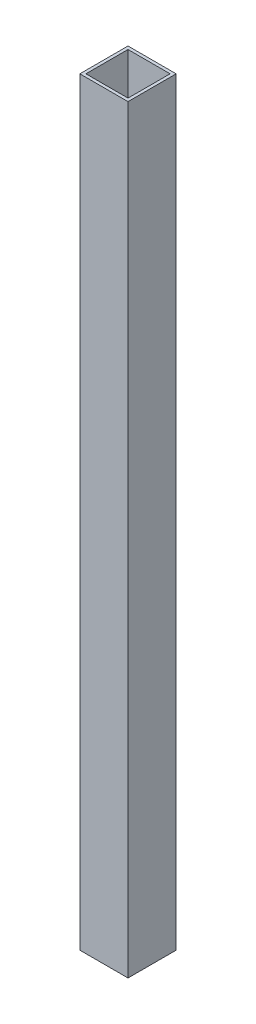
SolidWorks part; units mm, degrees
ref_plane "Front Plane" through (0, 0, 0) normal (0, 0, 1) x (1, 0, 0)
ref_plane "Top Plane" through (0, 0, 0) normal (0, 1, 0) x (1, 0, 0)
ref_plane "Right Plane" through (0, 0, 0) normal (1, 0, 0) x (0, 0, -1)
sketch "Sketch1" plane through (0, 0, 0) normal (0, 1, 0) x (1, 0, 0)
  line L1 (-25.4, -25.4) -> (25.4, -25.4)
  line L2 (-25.4, -25.4) -> (-25.4, 25.4)
  line L3 (-25.4, 25.4) -> (25.4, 25.4)
  line L4 (25.4, -25.4) -> (25.4, 25.4)
  line L5 (-25.4, -25.4) -> (25.4, 25.4) construction
  line L6 (-25.4, 25.4) -> (25.4, -25.4) construction
  line L7 (22.225, -22.225) -> (-22.225, -22.225)
  line L8 (22.225, -22.225) -> (22.225, 22.225)
  line L9 (22.225, 22.225) -> (-22.225, 22.225)
  line L10 (-22.225, -22.225) -> (-22.225, 22.225)
  line L11 (22.225, -22.225) -> (-22.225, 22.225) construction
  line L12 (22.225, 22.225) -> (-22.225, -22.225) construction
  point P0 (0, 0)
  point P6 (0, 0)
  dimension "D1" = 50.8
  dimension "D2" = 50.8
  dimension "D3" = 3.175
  dimension "D4" = 3.175
extrude "Boss-Extrude1" add sketch "Sketch1" along normal blind 800.8112
